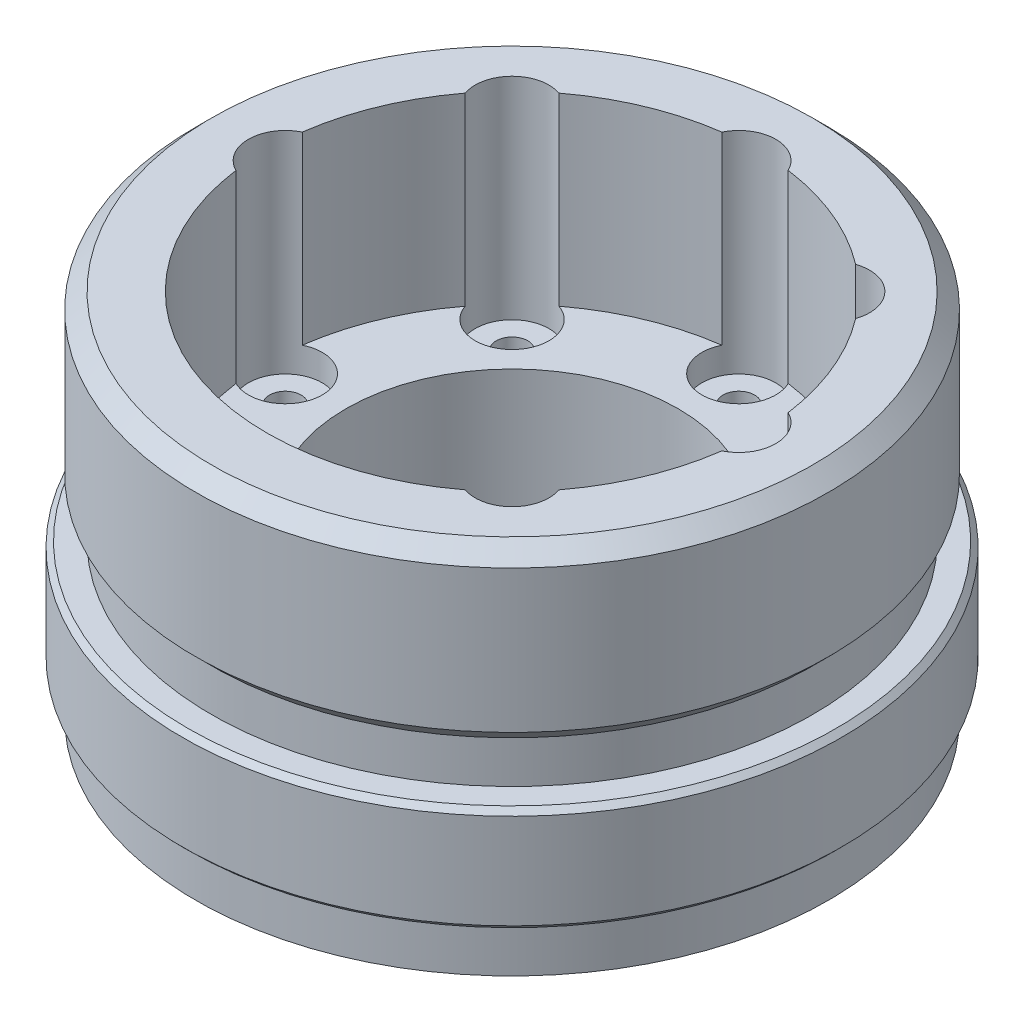
SolidWorks part; units mm, degrees
material "Алюминиевая бронза"
ref_plane "Спереди" through (0, 0, 0) normal (0, 0, 1) x (1, 0, 0)
ref_plane "Сверху" through (0, 0, 0) normal (0, 1, 0) x (1, 0, 0)
ref_plane "Справа" through (0, 0, 0) normal (1, 0, 0) x (0, 0, -1)
other "Табл. исп."
sketch "Эскиз1" plane through (0, 0, 0) normal (0, 0, 1) x (1, 0, 0)
  line L0 (0, 0) -> (0, 68.0615) construction
  line L1 (-42, 0) -> (-60, 0)
  line L2 (-60, 0) -> (-60, 9)
  line L3 (-60, 9) -> (-61.5, 9)
  line L4 (-62.5, 10) -> (-62.5, 28)
  line L5 (-62.5, 28) -> (-61.5, 29)
  line L6 (-61.5, 29) -> (-57, 29)
  line L7 (-57, 29) -> (-57, 37)
  line L8 (-57, 37) -> (-60, 40)
  line L9 (-60, 40) -> (-60, 67)
  line L10 (-60, 67) -> (-57, 70)
  line L11 (-57, 70) -> (-46.5, 70)
  line L12 (-46.5, 70) -> (-46.5, 35)
  line L13 (-46.5, 35) -> (-31.5, 35)
  line L14 (-31.5, 35) -> (-31.5, 10)
  line L15 (-31.5, 10) -> (-42, 10)
  line L16 (-42, 10) -> (-42, 0)
  line L17 (-61.5, 9) -> (-62.5, 10)
  dimension "D1" = 84
  dimension "D2" = 120
  dimension "D3" = 9
  dimension "D4" = 125
  dimension "D5" = 45
  dimension "D6" = 1
  dimension "D7" = 10
  dimension "D8" = 63
  dimension "D9" = 25
  dimension "D10" = 120
  dimension "D11" = 114
  dimension "D12" = 45
  dimension "D13" = 3
  dimension "D14" = 93
  dimension "D15" = 8
  dimension "D16" = 70
  dimension "D17" = 29
revolve "Повернуть1" add sketch "Эскиз1" angle 360 about L0
sketch "Эскиз5" plane through (0, 0, 0) normal (0, 0, 1) x (1, 0, 0)
  line L0 (-43, 84.5121) -> (-43, -16.1088) construction
  line L1 (-43, 0) -> (-46, 0)
  line L2 (-46, 0) -> (-46, 30)
  line L3 (-46, 30) -> (-50, 30)
  line L4 (-50, 30) -> (-50, 70)
  line L5 (-50, 70) -> (-43, 70)
  line L6 (-43, 70) -> (-43, 0)
  line L7 (31.5, 35) -> (-31.5, 35) construction
  line L8 (46.5, 70) -> (-46.5, 70) construction
  line L9 (-42, 0) -> (42, 0) construction
  dimension "D1" = 43
  dimension "D2" = 6
  dimension "D3" = 5
  dimension "D4" = 14
revolve "Вырез-Повернуть1" cut sketch "Эскиз5" angle 360 about L0
pattern_circular "Круговой массив1" count 8 over 360 about axis through (0, 0, 0) along (0, 1, 0) skipping 6, 7 of "Вырез-Повернуть1"
